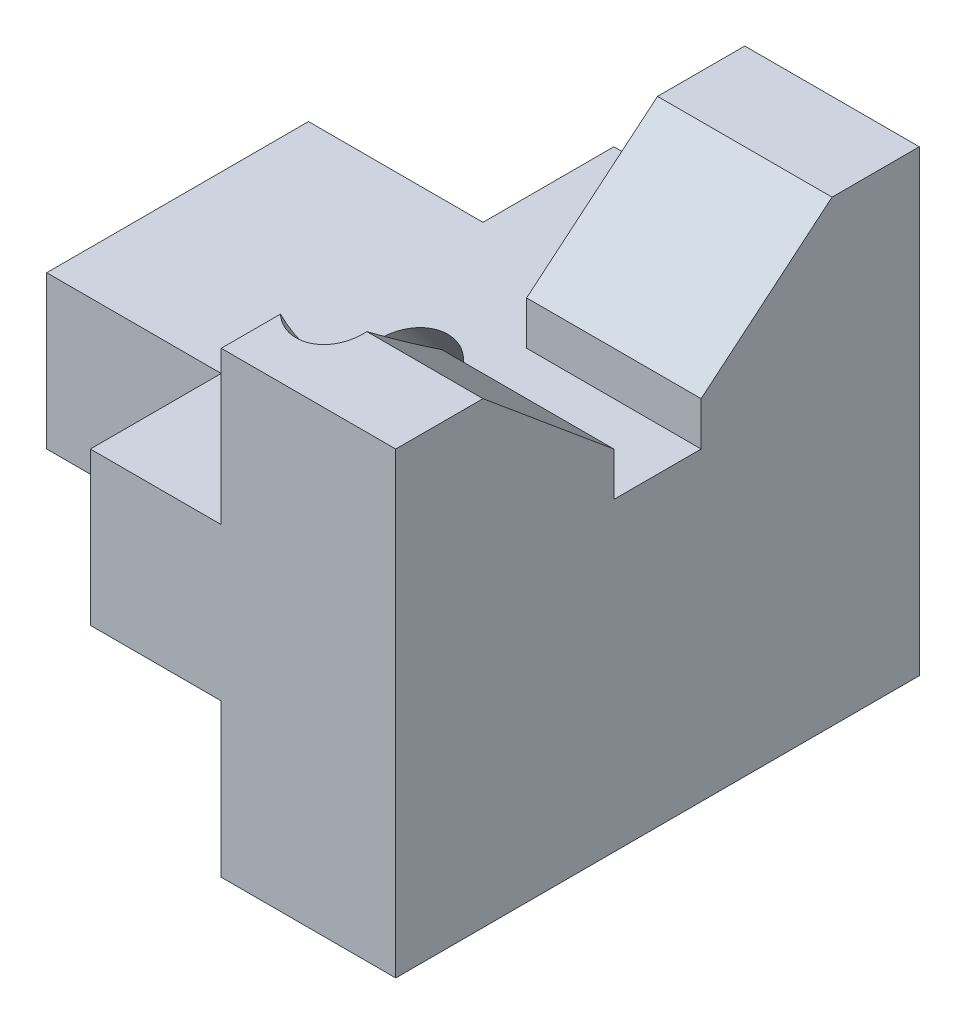
SolidWorks part; units mm, degrees
ref_plane "Front Plane" through (0, 0, 0) normal (0, 0, 1) x (1, 0, 0)
ref_plane "Top Plane" through (0, 0, 0) normal (0, 1, 0) x (1, 0, 0)
ref_plane "Right Plane" through (0, 0, 0) normal (1, 0, 0) x (0, 0, -1)
other "Center of Mass"
sketch "Sketch2" plane through (0, 0, 0) normal (1, 0, 0) x (0, 0, -1)
  line L0 (38.1, 0) -> (38.1, 66.675)
  line L1 (38.1, 66.675) -> (25.4, 66.675)
  line L2 (25.4, 66.675) -> (6.35, 50.8)
  line L3 (6.35, 50.8) -> (6.35, 44.45)
  line L4 (6.35, 44.45) -> (-6.35, 44.45)
  line L6 (-6.35, 50.8) -> (-25.4, 66.675)
  line L7 (-25.4, 66.675) -> (-38.1, 66.675)
  line L8 (-38.1, 66.675) -> (-38.1, 0)
  line L9 (-38.1, 0) -> (38.1, 0)
  line L10 (0, -31.1248) -> (0, 131.1373) construction
  line L11 (-6.35, 50.8) -> (-6.35, 44.45)
  dimension "D1" = 66.675
  dimension "D2" = 12.7
  dimension "D3" = 19.05
  dimension "D4" = 6.35
  dimension "D5" = 76.2
  dimension "D6" = 22.225
extrude "Boss-Extrude1" add sketch "Sketch2" along normal blind 25.4 contours L4 L11 L6 L7 L8 L9 L0 L1 L2 L3
sketch "Sketch3" plane through (0, 44.45, 0) normal (0, 1, 0) x (1, 0, 0)
  line L0 (0, 6.35) -> (0, 38.1)
  line L1 (0, 38.1) -> (-19.05, 38.1)
  line L2 (-19.05, 38.1) -> (-19.05, 19.05)
  line L3 (-19.05, 19.05) -> (-44.45, 19.05)
  line L4 (-44.45, 19.05) -> (-44.45, -19.05)
  line L5 (-44.45, -19.05) -> (-19.05, -19.05)
  line L6 (-19.05, -19.05) -> (-19.05, -38.1)
  line L7 (-19.05, -38.1) -> (0, -38.1)
  line L8 (0, -38.1) -> (0, -6.35)
  line L9 (0, -6.35) -> (0, 6.35)
  dimension "D1" = 19.05
  dimension "D2" = 38.1
  dimension "D3" = 25.4
  dimension "D4" = 19.05
extrude "Boss-Extrude2" add sketch "Sketch3" against normal blind 22.225
ref_plane "mplane" through (2.1712, -7.1017, 0) normal (0.2924, -0.9563, 0) x (0, 0, -1)
ref_plane "Plane8" through (8.9807, 22.5801, 19.7575) normal (0.2868, 0.721, 0.6309) x (0.958, -0.2158, -0.1888)
sketch "Sketch5" plane through (8.9807, 22.5801, 19.7575) normal (0.2868, 0.721, 0.6309) x (0.958, -0.2158, -0.1888)
  circle A0 centre (-16.337, 25.6908) radius 5.3733
extrude "Cut-Extrude1" cut sketch "Sketch5" along normal mid plane 121.285
ref_point "Point1"
sketch "Sketch6" plane through (0, 0, 38.1) normal (0, 0, 1) x (1, 0, 0)
  text T0 "Stacie is Awsome."
extrude "Boss-Extrude3" add sketch "Sketch6" against normal blind 2.54
